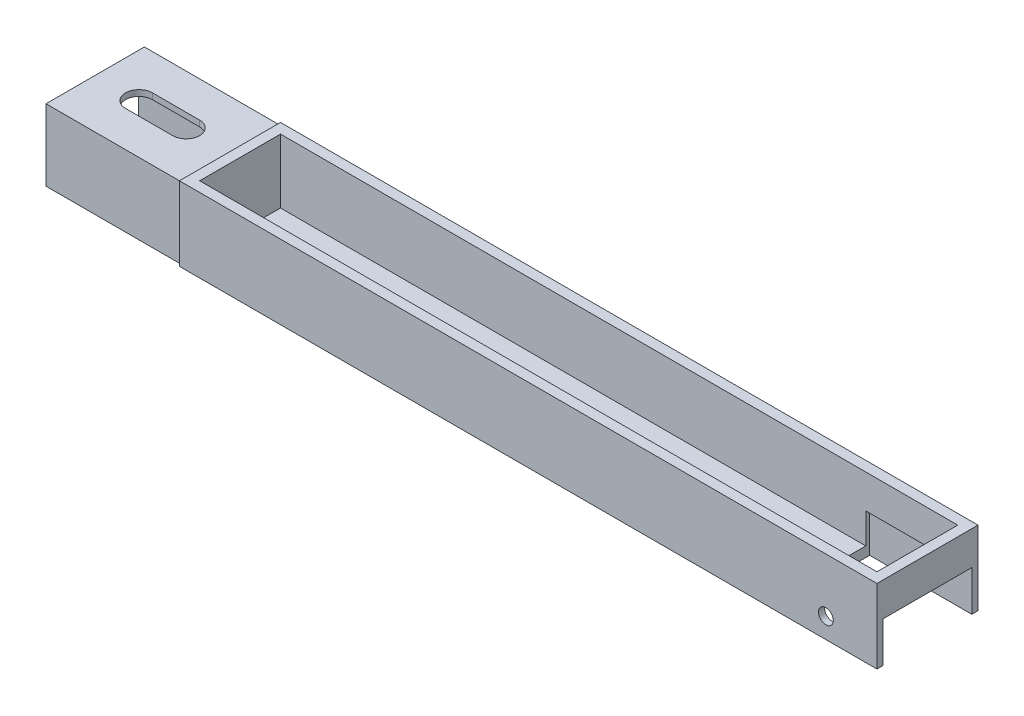
SolidWorks part; units mm, degrees
ref_plane "Front Plane" through (0, 0, 0) normal (0, 0, 1) x (1, 0, 0)
ref_plane "Top Plane" through (0, 0, 0) normal (0, 1, 0) x (1, 0, 0)
ref_plane "Right Plane" through (0, 0, 0) normal (1, 0, 0) x (0, 0, -1)
sketch "Sketch1" plane through (0, 0, 0) normal (0, 1, 0) x (1, 0, 0)
  line L1 (-103.5, -15) -> (103.5, -15)
  line L2 (-103.5, -15) -> (-103.5, 15)
  line L3 (-103.5, 15) -> (103.5, 15)
  line L4 (103.5, -15) -> (103.5, 15)
  line L5 (-103.5, -15) -> (103.5, 15) construction
  line L6 (-103.5, 15) -> (103.5, -15) construction
  point P0 (0, 0)
  dimension "D1" = 207
  dimension "D2" = 30
extrude "Boss-Extrude1" add sketch "Sketch1" along normal blind 22
shell "Shell1" thickness 3
sketch "Sketch2" plane through (0, 0, 0) normal (0, -1, 0) x (-1, 0, 0)
  line L0 (103.5, 15) -> (103.5, -15) construction
  line L1 (103.5, 5) -> (-103.5, 5)
  line L2 (103.5, 5) -> (103.5, -5)
  line L3 (103.5, -5) -> (-103.5, -5)
  line L4 (-103.5, 5) -> (-103.5, -5)
  line L5 (103.5, 5) -> (-103.5, -5) construction
  line L6 (103.5, -5) -> (-103.5, 5) construction
  point P0 (0, 0)
  dimension "D1" = 10
  dimension "D2" = 0
extrude "Cut-Extrude1" cut sketch "Sketch2" against normal blind 3
sketch "Sketch3" plane through (-103.5, 0, 0) normal (-1, 0, 0) x (0, 0, 1)
  line L0 (0, 22) -> (0, 0) construction
  line L1 (-14.6, 0.4) -> (14.6, 0.4)
  line L2 (-14.6, 0.4) -> (-14.6, 21.6)
  line L3 (-14.6, 21.6) -> (14.6, 21.6)
  line L4 (14.6, 0.4) -> (14.6, 21.6)
  line L5 (-14.6, 0.4) -> (14.6, 21.6) construction
  line L6 (-14.6, 21.6) -> (14.6, 0.4) construction
  line L7 (-15, 22) -> (15, 22) construction
  line L8 (-15, 11) -> (15, 11) construction
  line L9 (-15, 22) -> (-15, 0) construction
  line L10 (15, 22) -> (15, 0) construction
  point P0 (0, 11)
  dimension "D1" = 29.2
  dimension "D2" = 21.2
extrude "Boss-Extrude2" add sketch "Sketch3" along normal blind 40
sketch "Sketch4" plane through (-143.5, 0, 0) normal (-1, 0, 0) x (0, 0, 1)
  line L0 (0, 21.6) -> (0, 0.4) construction
  line L1 (-12.85, 2.15) -> (12.85, 2.15)
  line L2 (-12.85, 2.15) -> (-12.85, 19.85)
  line L3 (-12.85, 19.85) -> (12.85, 19.85)
  line L4 (12.85, 2.15) -> (12.85, 19.85)
  line L5 (-12.85, 2.15) -> (12.85, 19.85) construction
  line L6 (-12.85, 19.85) -> (12.85, 2.15) construction
  line L7 (14.6, 21.6) -> (-14.6, 21.6) construction
  line L8 (-14.6, 0.4) -> (14.6, 0.4) construction
  line L9 (-14.6, 11) -> (14.6, 11) construction
  line L10 (-14.6, 21.6) -> (-14.6, 0.4) construction
  line L11 (14.6, 0.4) -> (14.6, 21.6) construction
  point P0 (0, 11)
  dimension "D1" = 25.7
  dimension "D2" = 17.7
extrude "Cut-Extrude2" cut sketch "Sketch4" against normal blind 40
sketch "Sketch5" plane through (0, 21.6, 0) normal (0, 1, 0) x (1, 0, 0)
  line L0 (-130.5, 0) -> (-116.5, 0) construction
  line L1 (-130.5, 4) -> (-116.5, 4)
  line L2 (-130.5, -4) -> (-116.5, -4)
  line L3 (-103.5, 0) -> (-143.5, 0) construction
  line L4 (-103.5, -14.6) -> (-103.5, 14.6) construction
  line L5 (-143.5, -14.6) -> (-143.5, 14.6) construction
  arc A0 (-130.5, 4) -> (-130.5, -4) centre (-130.5, 0) ccw
  arc A1 (-116.5, -4) -> (-116.5, 4) centre (-116.5, 0) ccw
  point P2 (-123.5, 0)
  dimension "D1" = 14
  dimension "D2" = 8
  dimension "D3" = 20
extrude "Cut-Extrude3" cut sketch "Sketch5" against normal through all
sketch "Sketch6" plane through (0, 0, 0) normal (0, -1, 0) x (-1, 0, 0)
  line L0 (103.5, -5) -> (103.5, -15) construction
  line L1 (-73.2, -13.15) -> (-103.5, -13.15)
  line L2 (-73.2, -13.15) -> (-73.2, 13.15)
  line L3 (-73.2, 13.15) -> (-103.5, 13.15)
  line L4 (-103.5, -13.15) -> (-103.5, 13.15)
  line L5 (-73.2, -13.15) -> (-103.5, 13.15) construction
  line L6 (-73.2, 13.15) -> (-103.5, -13.15) construction
  line L7 (-103.5, 15) -> (103.5, 15) construction
  point P0 (-88.35, 0)
  dimension "D1" = 30.3
  dimension "D2" = 26.3
  dimension "D3" = 191.85
  dimension "D4" = 15
extrude "Cut-Extrude4" cut sketch "Sketch6" against normal blind 12
sketch "Sketch7" plane through (0, 0, 15) normal (0, 0, 1) x (1, 0, 0)
  line L0 (-103.5, 22) -> (-103.5, 0) construction
  line L1 (-103.5, 0) -> (103.5, 0) construction
  circle A0 centre (88.35, 6) radius 2.2
  dimension "D1" = 4.4
  dimension "D2" = 191.85
  dimension "D3" = 6
extrude "Cut-Extrude5" cut sketch "Sketch7" against normal through all
